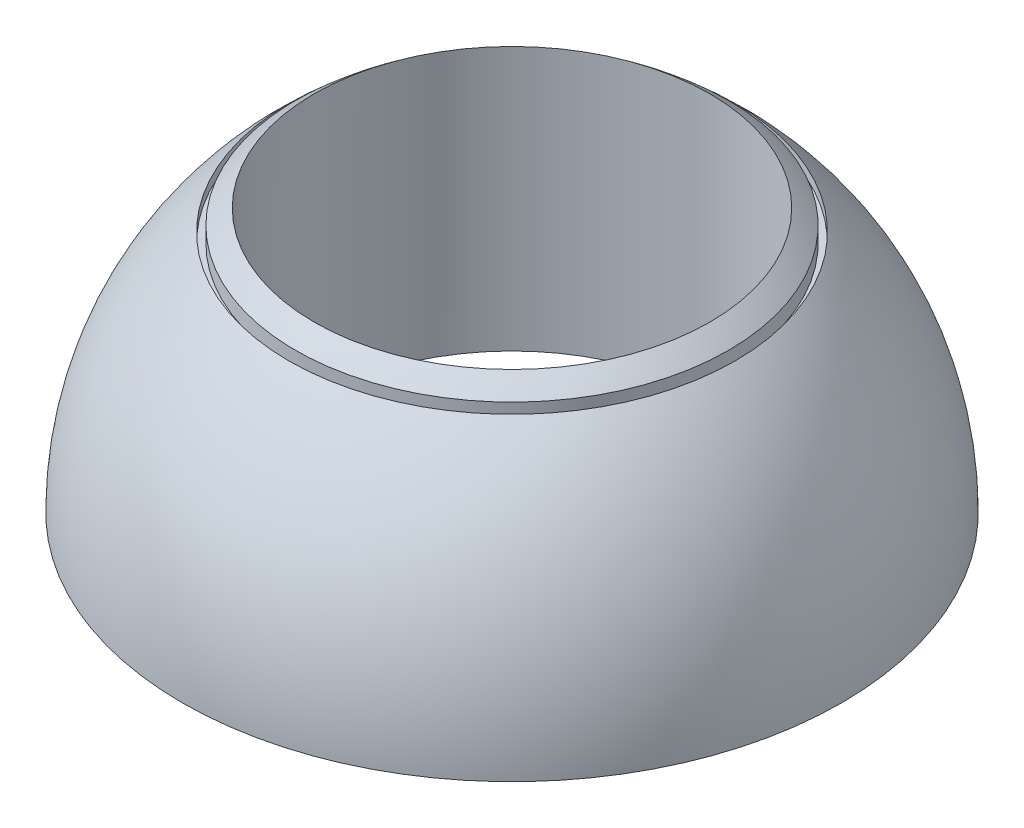
SolidWorks part; units mm, degrees
ref_plane "Front Plane" through (0, 0, 0) normal (0, 0, 1) x (1, 0, 0)
ref_plane "Top Plane" through (0, 0, 0) normal (0, 1, 0) x (1, 0, 0)
ref_plane "Right Plane" through (0, 0, 0) normal (1, 0, 0) x (0, 0, -1)
sketch "Sketch1" plane through (0, 0, 0) normal (0, 0, 1) x (1, 0, 0)
  line L0 (0, 0) -> (5, 0) construction
  line L1 (0, 0) -> (0, 2.7431) construction
  line L2 (0, 0) -> (3, 0) construction
  line L3 (3, 0) -> (3, 4)
  line L4 (3, 0) -> (5, 0)
  arc A0 (5, 0) -> (3, 4) centre (0, 0) ccw
  dimension "D1" = 5
  dimension "D2" = 3
revolve "Revolve1" add sketch "Sketch1" angle 360 about L1
sketch "Sketch2" plane through (0, 0, 0) normal (1, 0, 0) x (0, 0, -1)
  line L4 (3.2831, 3.7711) -> (3.2831, 3.5372)
  line L5 (3.2831, 3.5372) -> (3.3831, 3.5372)
  line L6 (3.3831, 3.5372) -> (3.3831, 3.7838)
  line L7 (3.2831, 3.7711) -> (3.2831, 3.9154)
  line L8 (3.2831, 3.9154) -> (3.3831, 3.9154)
  line L9 (3.3831, 3.9154) -> (3.3831, 3.7838)
  line L10 (0, 0) -> (0, 5.8992) construction
  dimension "D1" = 0.1
  dimension "D2" = 0.2466
revolve "Cut-Revolve1" cut sketch "Sketch2" angle 360 about L10
sketch "Sketch3" plane through (0, 0, 0) normal (0, -1, 0) x (1, 0, 0)
  line L0 (0, 0) -> (0, 0.5) construction
  line L1 (0, 0) -> (0, -0.5) construction
  line L2 (0, -0.5) -> (-4.9749, -0.5) construction
  line L3 (0, 0.5) -> (4.9749, 0.5) construction
  circle A0 centre (0, 0) radius 5 construction
  dimension "D1" = 0.5
  dimension "D2" = 0.5
